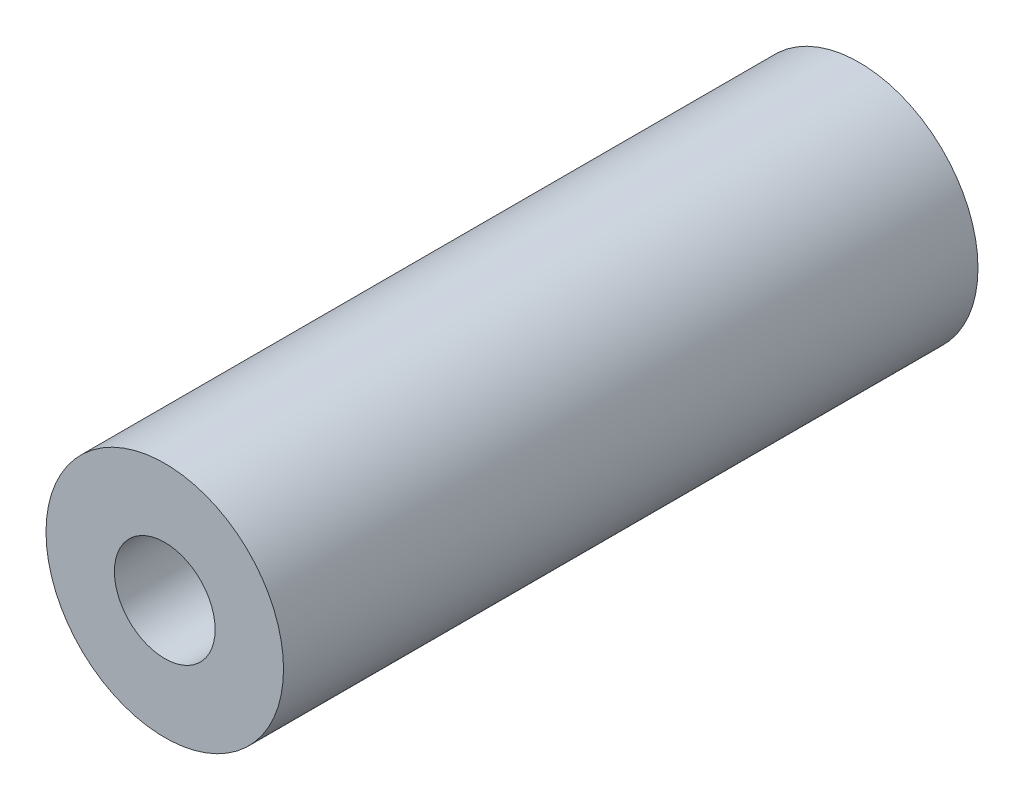
SolidWorks part; units mm, degrees
ref_plane "Front Plane" through (0, 0, 0) normal (0, 0, 1) x (1, 0, 0)
ref_plane "Top Plane" through (0, 0, 0) normal (0, 1, 0) x (1, 0, 0)
ref_plane "Right Plane" through (0, 0, 0) normal (1, 0, 0) x (0, 0, -1)
sketch "Sketch1" plane through (0, 0, 0) normal (0, 0, 1) x (1, 0, 0)
  circle A0 centre (0, 0) radius 4.7625
  dimension "D1" = 9.525
extrude "Boss-Extrude1" add sketch "Sketch1" along normal mid plane 27.8496
hole_wizard "#10-32 Tapped Hole1" positions "3DSketch1" profile "Sketch2" tap size "#10-32" standard "ANSI Inch"
sketch3d "3DSketch1"
  line L0 (0, 0, 13.9248) -> (0, 0, -13.9248) construction
  point P0 (0, 0, 13.9248)
  point P4 (0, 0, -13.9248)
sketch "Sketch2" plane through (0, 0, 13.9248) normal (1, 0, 0) x (0, -1, 0)
  line L0 (0, 0) -> (0, 16.1993)
  line L1 (0, 16.1993) -> (2.0193, 14.986)
  line L2 (2.0193, 14.986) -> (2.0193, 0)
  line L5 (2.0193, 0) -> (0, 0)
  line L10 (0, 16.1993) -> (-2.0193, 14.986) construction
  line L11 (0, -6.35) -> (0, 107.95) construction
  dimension "Tap Drill Dia." = 4.0386
  dimension "Tap Drill Depth" = 14.986
  dimension "Drill Angle" = 118
cosmetic thread "Hole Thread1"
cosmetic thread "Hole Thread2"
